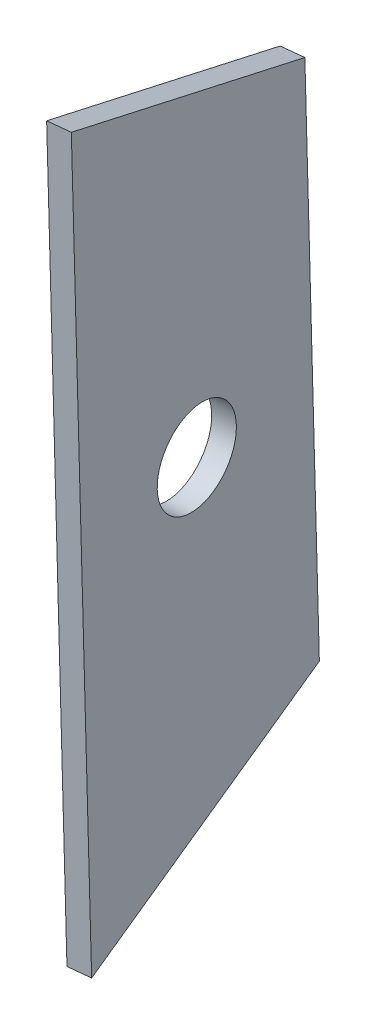
SolidWorks part; units mm, degrees
ref_plane "Front Plane" through (0, 0, 0) normal (0, 0, 1) x (1, 0, 0)
ref_plane "Top Plane" through (0, 0, 0) normal (0, 1, 0) x (1, 0, 0)
ref_plane "Right Plane" through (0, 0, 0) normal (1, 0, 0) x (0, 0, -1)
sketch "Sketch1" plane through (368.9369, -5.3839, -45.5872) normal (0.9923, -0.0145, -0.1226) x (-0.1226, 0.0018, -0.9925)
  line L0 (411.5941, 245.558) -> (414.1809, 191.185)
  line L1 (90.3213, 348.9052) -> (472.4727, 225.9745) construction
  line L2 (183.6443, 75.6122) -> (478.9871, 223.6738) construction
  line L3 (414.1809, 191.185) -> (432.7973, 200.5179)
  line L4 (432.7973, 200.5179) -> (430.9508, 239.3313)
  line L5 (430.9508, 239.3313) -> (411.5941, 245.558)
  line L6 (412.8875, 218.3715) -> (431.8741, 219.9246) construction
  circle A0 centre (422.3808, 219.1481) radius 3.2639
  point P13 (0, 0)
  point P14 (431.0609, 239.2959)
  dimension "D1" = 6.5278
  dimension "D2" = 19.05
extrude "Boss-Extrude1" add sketch "Sketch1" along normal blind 1.5875
